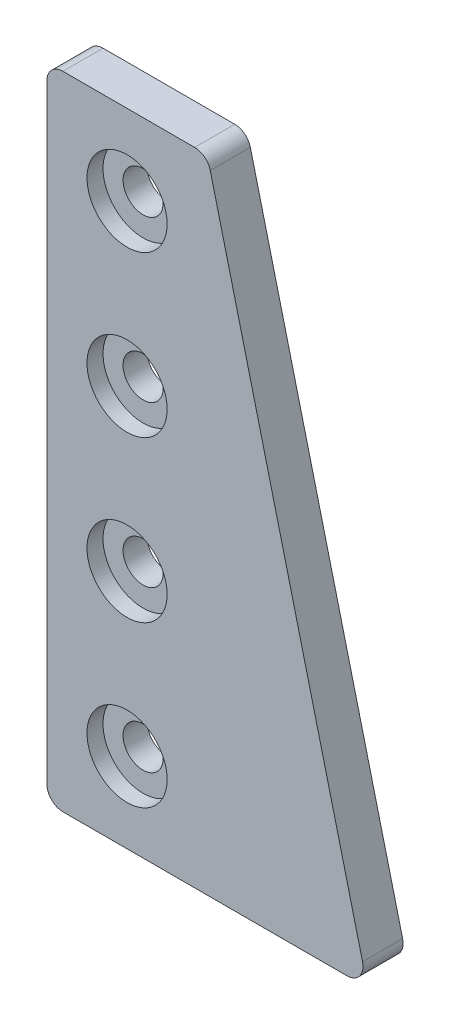
SolidWorks part; units mm, degrees
ref_plane "Front Plane" through (0, 0, 0) normal (0, 0, 1) x (1, 0, 0)
ref_plane "Top Plane" through (0, 0, 0) normal (0, 1, 0) x (1, 0, 0)
ref_plane "Right Plane" through (0, 0, 0) normal (1, 0, 0) x (0, 0, -1)
sketch "Sketch1" plane through (0, 0, 0) normal (0, 0, 1) x (1, 0, 0)
  line L0 (0, 0) -> (0, 80)
  line L1 (0, 80) -> (20, 80)
  line L2 (20, 80) -> (40, 0)
  line L3 (40, 0) -> (0, 0)
  dimension "D1" = 80
  dimension "D2" = 20
  dimension "D3" = 40
extrude "Boss-Extrude1" add sketch "Sketch1" along normal blind 5
sketch "Sketch2" plane through (0, 0, 5) normal (0, 0, 1) x (1, 0, 0)
  line L0 (10, 80) -> (10, 0) construction
  line L1 (20, 80) -> (0, 80) construction
  line L2 (0, 0) -> (40, 0) construction
  line L3 (0, 70) -> (22.5, 70) construction
  line L4 (0, 80) -> (0, 0) construction
  line L5 (40, 0) -> (20, 80) construction
  line L6 (0, 50) -> (27.5, 50) construction
  line L7 (0, 10) -> (37.5, 10) construction
  line L8 (0, 30) -> (32.5, 30) construction
  circle A0 centre (10, 70) radius 2.5
  circle A1 centre (10, 50) radius 2.5
  circle A2 centre (10, 30) radius 2.5
  circle A3 centre (10, 10) radius 2.5
  dimension "D3" = 5
  dimension "D4" = 5
  dimension "D7" = 5
  dimension "D8" = 5
  dimension "D1" = 10
  dimension "D2" = 20
  dimension "D5" = 10
  dimension "D6" = 20
extrude "Cut-Extrude1" cut sketch "Sketch2" against normal blind 10
sketch "Sketch3" plane through (0, 0, 5) normal (0, 0, 1) x (1, 0, 0)
  circle A0 centre (10, 70) radius 5
  circle A1 centre (10, 50) radius 5
  circle A2 centre (10, 30) radius 5
  circle A3 centre (10, 10) radius 5
  dimension "D1" = 10
  dimension "D2" = 10
  dimension "D3" = 10
  dimension "D4" = 10
extrude "Cut-Extrude2" cut sketch "Sketch3" against normal blind 2
fillet "Fillet1" radius 2 4 edges at (0, 0, 2.5) (40, 0, 2.5) (20, 80, 2.5) (0, 80, 2.5)
